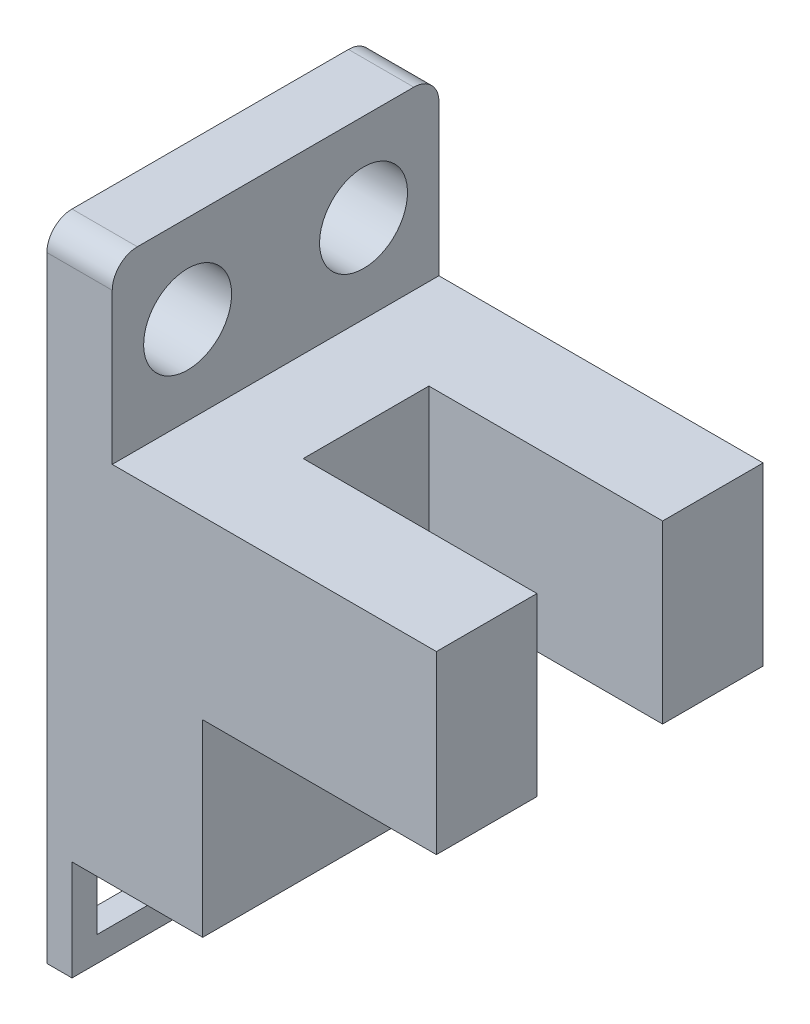
SolidWorks part; units mm, degrees
ref_plane "前视基准面" through (0, 0, 0) normal (0, 0, 1) x (1, 0, 0)
ref_plane "上视基准面" through (0, 0, 0) normal (0, 1, 0) x (1, 0, 0)
ref_plane "右视基准面" through (0, 0, 0) normal (1, 0, 0) x (0, 0, -1)
sketch "草图1" plane through (0, 0, 0) normal (0, 0, 1) x (1, 0, 0)
  line L0 (0, 0) -> (9.3, 0)
  line L1 (9.3, 0) -> (9.3, 7)
  line L2 (9.3, 7) -> (-6.2, 7)
  line L3 (-6.2, 7) -> (-6.2, -7.5)
  line L4 (-6.2, -7.5) -> (0, -7.5)
  line L5 (0, -7.5) -> (0, 0)
  dimension "D1" = 7
  dimension "D2" = 6.2
  dimension "D3" = 9.3
  dimension "D4" = 7.5
extrude "凸台-拉伸1" add sketch "草图1" along normal mid plane 13
sketch "草图2" plane through (0, 0, 0) normal (0, -1, 0) x (1, 0, 0)
  line L0 (14.8182, 0) -> (-11.8306, 0) construction
  line L1 (9.3, 6.5) -> (9.3, -6.5) construction
  line L2 (0, 2.5) -> (9.3, 2.5)
  line L3 (0, 2.5) -> (0, -2.5)
  line L4 (0, -2.5) -> (9.3, -2.5)
  line L5 (9.3, 2.5) -> (9.3, -2.5)
  line L6 (0, 2.5) -> (9.3, -2.5) construction
  line L7 (0, -2.5) -> (9.3, 2.5) construction
  line L8 (0, 6.5) -> (0, -6.5) construction
  point P2 (4.65, 0)
  dimension "D1" = 5
extrude "切除-拉伸1" cut sketch "草图2" against normal through all
sketch "草图3" plane through (-6.2, 0, 0) normal (-1, 0, 0) x (0, 0, 1)
  line L0 (0, 16.1311) -> (0, -15.3091) construction
  line L1 (-10.2666, 10.5) -> (14.498, 10.5) construction
  line L2 (5.5, 14) -> (-5.5, 14)
  line L3 (6.5, 13) -> (6.5, 7)
  line L4 (6.5, 7) -> (-6.5, 7)
  line L5 (-6.5, 13) -> (-6.5, 7)
  line L6 (6.5, 14) -> (-6.5, 7) construction
  line L7 (6.5, 7) -> (-6.5, 14) construction
  circle A0 centre (-3.5, 10.5) radius 1.75
  circle A1 centre (3.5, 10.5) radius 1.75
  arc A2 (-6.5, 13) -> (-5.5, 14) centre (-5.5, 13) cw
  arc A3 (6.5, 13) -> (5.5, 14) centre (5.5, 13) ccw
  point P3 (0, 10.5)
  dimension "D2" = 3.5
  dimension "D4" = 1
  dimension "D5" = 1
  dimension "D1" = 7
  dimension "D3" = 7
extrude "凸台-拉伸2" add sketch "草图3" against normal blind 2.6
sketch "草图4" plane through (-6.2, 0, 0) normal (-1, 0, 0) x (0, 0, 1)
  line L0 (0, 4.1378) -> (0, -15.32) construction
  line L1 (-5.5, -10.5) -> (-5.5, -8.5)
  line L2 (6.5, -11.5) -> (-6.5, -11.5)
  line L3 (6.5, -11.5) -> (6.5, -7.5)
  line L4 (6.5, -7.5) -> (-6.5, -7.5)
  line L5 (-6.5, -11.5) -> (-6.5, -7.5)
  line L6 (6.5, -11.5) -> (-6.5, -7.5) construction
  line L7 (6.5, -7.5) -> (-6.5, -11.5) construction
  line L8 (5.5, -8.5) -> (-5.5, -8.5)
  line L9 (5.5, -10.5) -> (5.5, -8.5)
  line L10 (5.5, -10.5) -> (-5.5, -10.5)
  point P3 (0, -9.5)
  dimension "D1" = 4
  dimension "D2" = 1
extrude "凸台-拉伸3" add sketch "草图4" against normal blind 1
